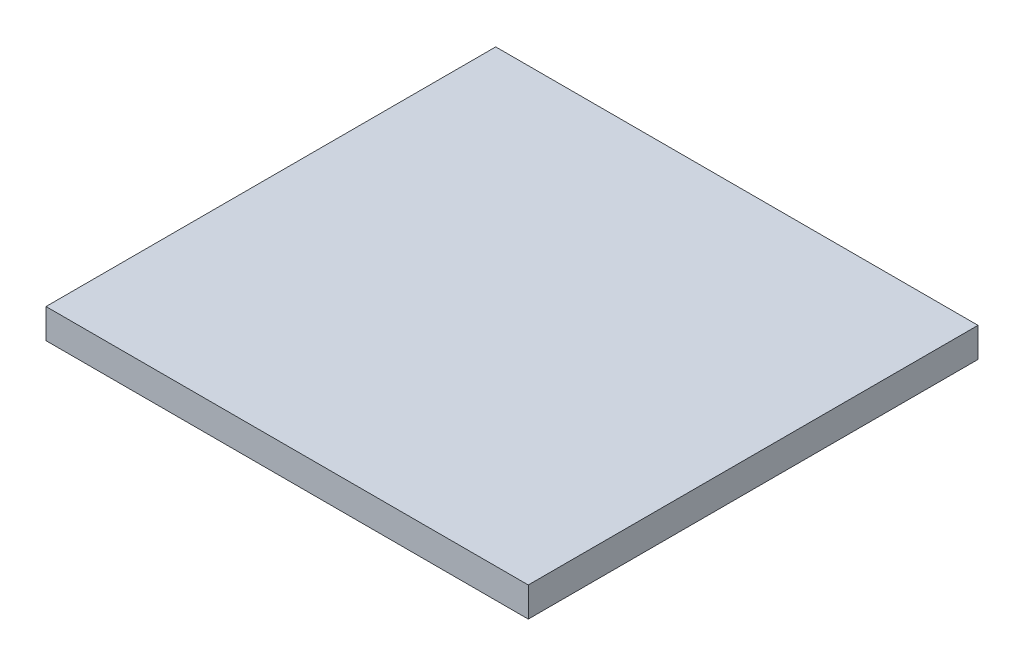
SolidWorks part; units mm, degrees
ref_plane "Ebene vorne" through (0, 0, 0) normal (0, 0, 1) x (1, 0, 0)
ref_plane "Ebene oben" through (0, 0, 0) normal (0, 1, 0) x (1, 0, 0)
ref_plane "Ebene rechts" through (0, 0, 0) normal (1, 0, 0) x (0, 0, -1)
sketch "Skizze1" plane through (0, 0, 0) normal (0, 1, 0) x (1, 0, 0)
  line L1 (8.15, -7.6) -> (-8.15, -7.6)
  line L2 (8.15, -7.6) -> (8.15, 7.6)
  line L3 (8.15, 7.6) -> (-8.15, 7.6)
  line L4 (-8.15, -7.6) -> (-8.15, 7.6)
  line L5 (8.15, -7.6) -> (-8.15, 7.6) construction
  line L6 (8.15, 7.6) -> (-8.15, -7.6) construction
  point P0 (0, 0)
  dimension "D1" = 15.2
  dimension "D2" = 16.3
extrude "Aufsatz-Linear austragen1" add sketch "Skizze1" along normal blind 1
